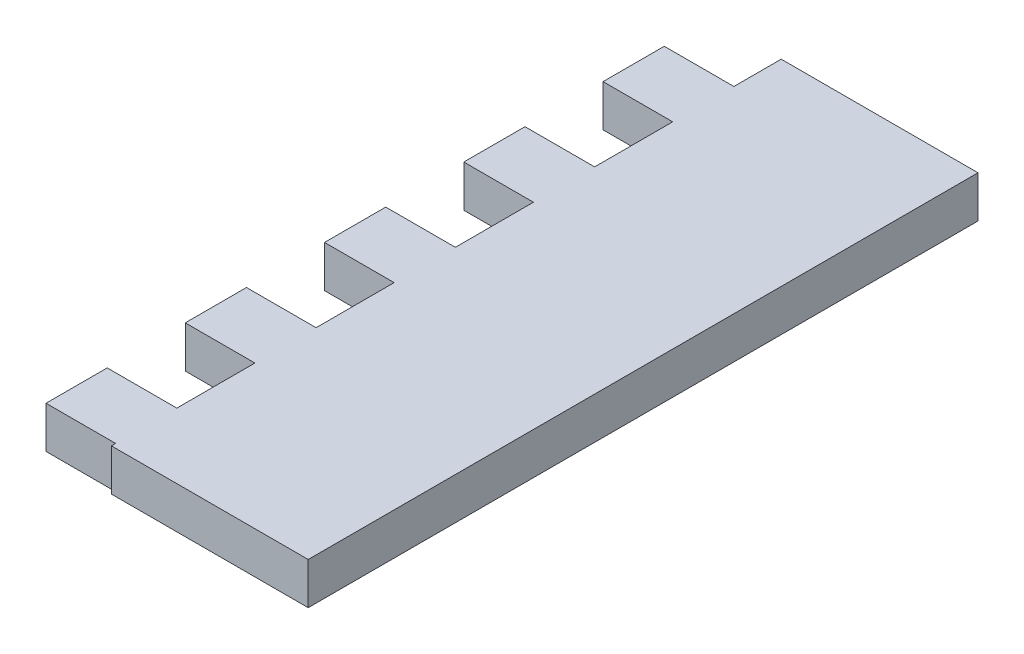
SolidWorks part; units mm, degrees
ref_plane "前视基准面" through (0, 0, 0) normal (0, 0, 1) x (1, 0, 0)
ref_plane "上视基准面" through (0, 0, 0) normal (0, 1, 0) x (1, 0, 0)
ref_plane "右视基准面" through (0, 0, 0) normal (1, 0, 0) x (0, 0, -1)
sketch "草图1" plane through (0, 0, 0) normal (0, 1, 0) x (1, 0, 0)
  line L1 (-9.5652, 25) -> (9.5652, 25)
  line L2 (-9.5652, 25) -> (-9.5652, -25)
  line L3 (-9.5652, -25) -> (9.5652, -25)
  line L4 (9.5652, 25) -> (9.5652, -25)
  line L5 (-9.5652, 25) -> (9.5652, -25) construction
  line L6 (-9.5652, -25) -> (9.5652, 25) construction
  point P0 (0, 0)
  dimension "D1" = 50
extrude "凸台-拉伸1" add sketch "草图1" along normal blind 3
sketch "草图2" plane through (0, 3, 0) normal (0, 1, 0) x (1, 0, 0)
  line L0 (-4.5652, 15) -> (-4.5652, 10)
  line L1 (-9.5652, 25) -> (-4.5652, 25)
  line L2 (-9.5652, 25) -> (-9.5652, 20)
  line L3 (-9.5652, 20) -> (-4.5652, 20)
  line L4 (-4.5652, 25) -> (-4.5652, 20)
  line L5 (-9.5652, 15) -> (-4.5652, 15)
  line L6 (-9.5652, 10) -> (-4.5652, 10)
  line L7 (-9.5652, 15) -> (-9.5652, 10)
  line L8 (-4.5652, 5) -> (-4.5652, 0)
  line L9 (-9.5652, 5) -> (-4.5652, 5)
  line L10 (-9.5652, 0) -> (-4.5652, 0)
  line L11 (-9.5652, 5) -> (-9.5652, 0)
  line L12 (-4.5652, -5) -> (-4.5652, -10)
  line L13 (-9.5652, -5) -> (-4.5652, -5)
  line L14 (-9.5652, -10) -> (-4.5652, -10)
  line L15 (-9.5652, -5) -> (-9.5652, -10)
  line L16 (-4.5652, -15) -> (-4.5652, -20)
  line L17 (-9.5652, -15) -> (-4.5652, -15)
  line L18 (-9.5652, -20) -> (-4.5652, -20)
  line L19 (-9.5652, -15) -> (-9.5652, -20)
  line L20 (-4.5652, 25) -> (-4.5652, 15) construction
  dimension "D1" = 5
  dimension "D2" = 5
  dimension "D4" = 10
  dimension "D3" = 5
extrude "切除-拉伸1" cut sketch "草图2" against normal blind 3
sketch "草图3" plane through (0, 3, 0) normal (0, 1, 0) x (1, 0, 0)
  line L1 (-6.0236, 27.7816) -> (12.0634, 27.7816)
  line L2 (-6.0236, 27.7816) -> (-6.0236, 23.0949)
  line L3 (-6.0236, 23.0949) -> (12.0634, 23.0949)
  line L4 (12.0634, 27.7816) -> (12.0634, 23.0949)
extrude "切除-拉伸2" cut sketch "草图3" against normal blind 3
sketch "草图4" plane through (0, 3, 0) normal (0, 1, 0) x (1, 0, 0)
  line L0 (-4.4866, 17.5) -> (-10.3233, 17.5) construction
  line L1 (-9.5652, 20) -> (-4.5652, 20) construction
  line L2 (-9.5652, 20.3027) -> (-4.5652, 20.3027)
  line L3 (-9.5652, 20.3027) -> (-9.5652, 19.6973)
  line L4 (-9.5652, 19.6973) -> (-4.5652, 19.6973)
  line L5 (-4.5652, 20.3027) -> (-4.5652, 19.6973)
  line L6 (-9.5652, 20.3027) -> (-4.5652, 19.6973) construction
  line L7 (-9.5652, 19.6973) -> (-4.5652, 20.3027) construction
  line L8 (-9.5652, 15.3027) -> (-4.5652, 15.3027)
  line L9 (-4.5652, 14.6973) -> (-4.5652, 15.3027)
  line L10 (-9.5652, 14.6973) -> (-4.5652, 14.6973)
  line L11 (-9.5652, 14.6973) -> (-9.5652, 15.3027)
  line L12 (-9.5652, 15.3027) -> (-4.5652, 14.6973) construction
  line L13 (-9.5652, 14.6973) -> (-4.5652, 15.3027) construction
  line L14 (-9.5652, 4.6973) -> (-4.5652, 4.6973)
  line L15 (-9.5652, 4.6973) -> (-9.5652, 5.3027)
  line L16 (-4.5652, 4.6973) -> (-4.5652, 5.3027)
  line L17 (-9.5652, 5.3027) -> (-4.5652, 5.3027)
  line L18 (-9.5652, 9.6973) -> (-4.5652, 9.6973)
  line L19 (-9.5652, 10.3027) -> (-4.5652, 10.3027)
  line L20 (-4.5652, 10.3027) -> (-4.5652, 9.6973)
  line L21 (-9.5652, 10.3027) -> (-9.5652, 9.6973)
  line L22 (-9.5652, -5.3027) -> (-4.5652, -5.3027)
  line L23 (-9.5652, -5.3027) -> (-9.5652, -4.6973)
  line L24 (-4.5652, -5.3027) -> (-4.5652, -4.6973)
  line L25 (-9.5652, -4.6973) -> (-4.5652, -4.6973)
  line L26 (-9.5652, -0.3027) -> (-4.5652, -0.3027)
  line L27 (-9.5652, 0.3027) -> (-4.5652, 0.3027)
  line L28 (-4.5652, 0.3027) -> (-4.5652, -0.3027)
  line L29 (-9.5652, 0.3027) -> (-9.5652, -0.3027)
  line L30 (-9.5652, -15.3027) -> (-4.5652, -15.3027)
  line L31 (-9.5652, -15.3027) -> (-9.5652, -14.6973)
  line L32 (-4.5652, -15.3027) -> (-4.5652, -14.6973)
  line L33 (-9.5652, -14.6973) -> (-4.5652, -14.6973)
  line L34 (-9.5652, -10.3027) -> (-4.5652, -10.3027)
  line L35 (-9.5652, -9.6973) -> (-4.5652, -9.6973)
  line L36 (-4.5652, -9.6973) -> (-4.5652, -10.3027)
  line L37 (-9.5652, -9.6973) -> (-9.5652, -10.3027)
  line L38 (-9.5652, -25.3027) -> (-4.5652, -25.3027)
  line L39 (-9.5652, -25.3027) -> (-9.5652, -24.6973)
  line L40 (-4.5652, -25.3027) -> (-4.5652, -24.6973)
  line L41 (-9.5652, -24.6973) -> (-4.5652, -24.6973)
  line L42 (-9.5652, -20.3027) -> (-4.5652, -20.3027)
  line L43 (-9.5652, -19.6973) -> (-4.5652, -19.6973)
  line L44 (-4.5652, -19.6973) -> (-4.5652, -20.3027)
  line L45 (-9.5652, -19.6973) -> (-9.5652, -20.3027)
  line L46 (-9.5652, 14.6973) -> (-9.5652, 4.6973) construction
  point P2 (-7.0652, 20)
  point P13 (-7.0652, 15)
  dimension "D2" = 10
  dimension "D1" = 5
extrude "切除-拉伸3" cut sketch "草图4" against normal blind 10
